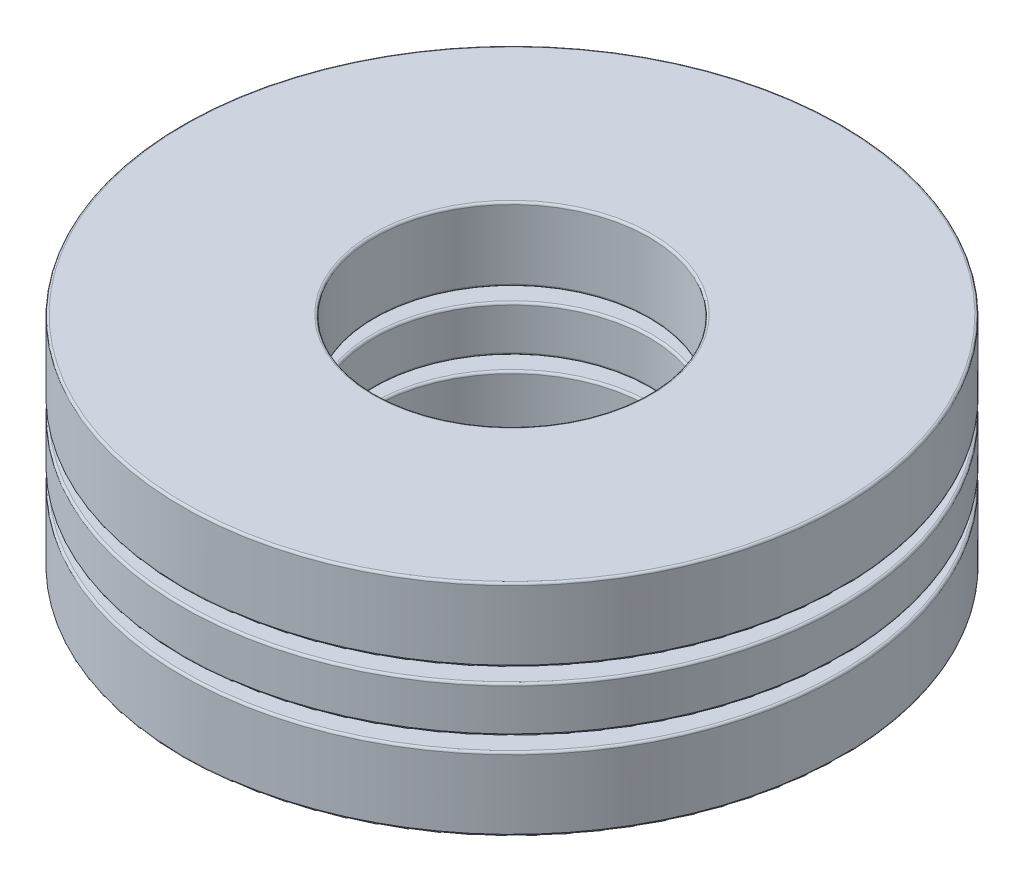
SolidWorks part; units mm, degrees
ref_plane "Front Plane" through (0, 0, 0) normal (0, 0, 1) x (1, 0, 0)
ref_plane "Top Plane" through (0, 0, 0) normal (0, 1, 0) x (1, 0, 0)
ref_plane "Right Plane" through (0, 0, 0) normal (1, 0, 0) x (0, 0, -1)
sketch "Sketch1" plane through (0, 0, 0) normal (1, 0, 0) x (0, 0, -1)
  line L0 (-6, 0) -> (6, 0) construction
  line L1 (0, -2) -> (0, 2) construction
  line L2 (-6, 0.4167) -> (-2.5, 0.4167)
  line L3 (-6, 0.4167) -> (-6, -0.4167)
  line L4 (-6, -0.4167) -> (-2.5, -0.4167)
  line L5 (-2.5, 0.4167) -> (-2.5, -0.4167)
  line L6 (-4.25, 0.6667) -> (-4.25, -0.6667) construction
  circle A0 centre (-4.25, 0) radius 0.6667 construction
  point P13 (-4.25, 0.4167)
  dimension "OD" = 12
  dimension "Shaft Dia" = 5
  dimension "Th" = 4
  dimension "D1" = 1.3333
  dimension "D2" = 0.8333
revolve "Revolve1" add sketch "Sketch1" angle 360 about L1
sketch "Sketch3" plane through (0, 0, 0) normal (1, 0, 0) x (0, 0, -1)
  line L0 (-4.25, 0.6667) -> (-4.25, -0.6667)
  arc A0 (-4.25, 0.6667) -> (-4.25, -0.6667) centre (-4.25, 0) ccw
  circle A1 centre (-4.25, 0) radius 0.6667 construction
revolve "Cut-Revolve1" cut sketch "Sketch3" angle 360 about L0
sketch "Sketch2" plane through (0, 0, 0) normal (1, 0, 0) x (0, 0, -1)
  line L0 (-4.25, 0.6667) -> (-4.25, -0.6667)
  arc A0 (-4.25, 0.6667) -> (-4.25, -0.6667) centre (-4.25, 0) ccw
  circle A2 centre (-4.25, 0) radius 0.6667 construction
revolve "Revolve2" add sketch "Sketch2" angle 360 about L0
ref_axis "Axis1" through (0, 2, 0) along (0, -1, 0)
pattern_circular "CirPattern1" count 3 every 120 about axis through (0, 2, 0) along (0, -1, 0) of bodies 187
pattern_circular "CirPattern2" count 3 every 120 about axis through (0, 0, 0) along (0, 1, 0) of "Cut-Revolve1"
sketch "Sketch4" plane through (0, 0, 0) normal (1, 0, 0) x (0, 0, -1)
  line L0 (-6, 0.4167) -> (-6, -0.4167) construction
  line L1 (-6, 0.6667) -> (-2.5, 0.6667)
  line L2 (-6, 0.6667) -> (-6, 2)
  line L3 (-6, 2) -> (-2.5, 2)
  line L4 (-2.5, 0.6667) -> (-2.5, 2)
  line L5 (-6, -2) -> (-2.5, -2)
  line L6 (-6, -2) -> (-6, -0.6667)
  line L7 (-6, -0.6667) -> (-2.5, -0.6667)
  line L8 (-2.5, -2) -> (-2.5, -0.6667)
  line L9 (-4.25, 0.6667) -> (-4.25, -0.6667) construction
  line L10 (-2.5, 0.4167) -> (-2.5, -0.4167) construction
  line L11 (0, 0) -> (-6, 0) construction
  line L12 (-6, 0) -> (6, 0) construction
  dimension "Ht" = 4
revolve "Revolve3" add sketch "Sketch4" angle 360 about L1
fillet "Fillet1" radius 0.04 4 edges at (0, 0.6667, -2.5) (0, 2, -2.5) (0, 0.6667, -6) (0, 2, -6)
fillet "Fillet2" radius 0.04 4 edges at (0, -0.4167, -2.5) (0, 0.4167, -2.5) (0, -0.4167, -6) (0, 0.4167, -6)
fillet "Fillet3" radius 0.04 4 edges at (0, -2, -2.5) (0, -0.6667, -2.5) (0, -2, -6) (0, -0.6667, -6)
equation "\"D1@Sketch1\" = \"Th@Sketch1\"/3"
equation "\"D2@Sketch1\" = \"D1@Sketch1\"*.625"
equation "\"Balls@CirPattern1\" = \"OD@Sketch1\"*.25"
equation "\"Angle@CirPattern1\" = 360/\"Balls@CirPattern1\""
equation "\"D1@CirPattern2\" = \"Balls@CirPattern1\""
equation "\"D2@CirPattern2\" = \"Angle@CirPattern1\""
equation "\"D1@Fillet1\" = \"Th@Sketch1\"*.01"
equation "\"D1@Fillet2\" = \"D1@Fillet1\""
equation "\"D1@Fillet3\" = \"D1@Fillet1\""
